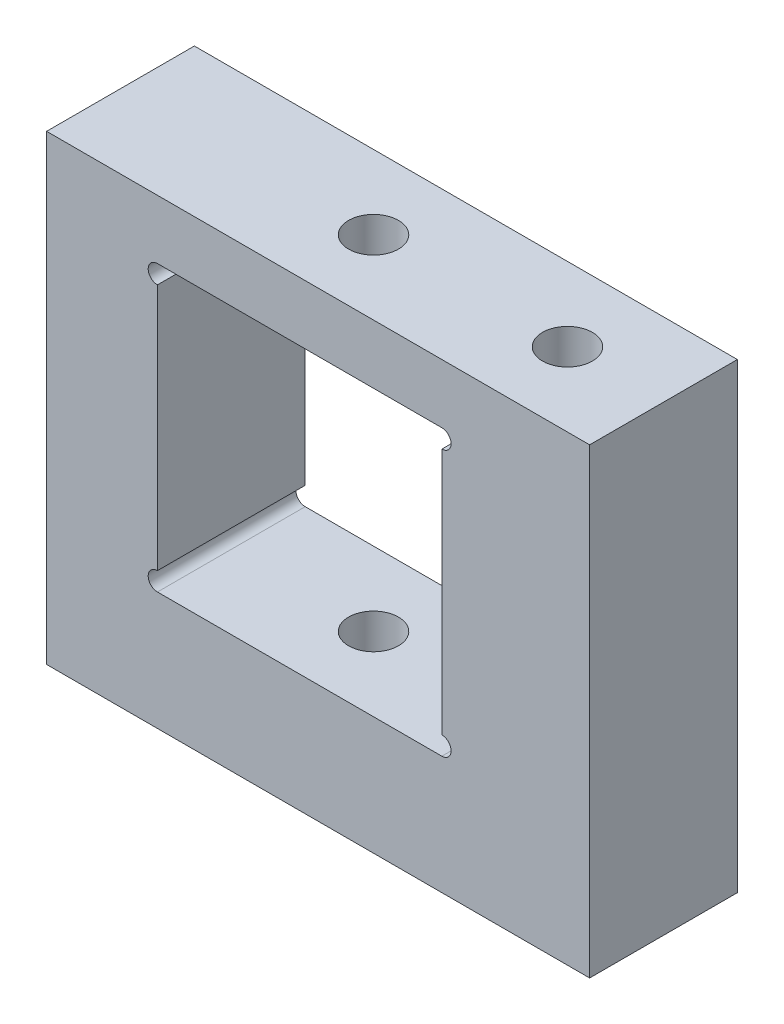
SolidWorks part; units mm, degrees
material "PLA"
ref_plane "前视基准面" through (0, 0, 0) normal (0, 0, 1) x (1, 0, 0)
ref_plane "上视基准面" through (0, 0, 0) normal (0, 1, 0) x (1, 0, 0)
ref_plane "右视基准面" through (0, 0, 0) normal (1, 0, 0) x (0, 0, -1)
sketch "草图2" plane through (0, 0, 0) normal (0, 0, 1) x (1, 0, 0)
  line L0 (-13.7, 10.9) -> (15.7, 10.9)
  line L1 (7.7, -7.7) -> (-7.7, -7.7)
  line L2 (7.7, -7.7) -> (7.7, 7.7)
  line L3 (7.7, 7.7) -> (-7.7, 7.7)
  line L4 (-7.7, -7.7) -> (-7.7, 7.7)
  line L5 (7.7, -7.7) -> (-7.7, 7.7) construction
  line L6 (7.7, 7.7) -> (-7.7, -7.7) construction
  line L7 (15.7, 10.9) -> (15.7, -14.1)
  line L8 (15.7, -14.1) -> (-13.7, -14.1)
  line L9 (-13.7, -14.1) -> (-13.7, 10.9)
  line L10 (0, 0) -> (-11.4797, 0) construction
  circle A0 centre (-7.7, 7.2) radius 0.5
  circle A1 centre (7.7, 7.2) radius 0.5
  circle A2 centre (7.7, -7.2) radius 0.5
  circle A3 centre (-7.7, -7.2) radius 0.5
  point P0 (0, 0)
  dimension "D2" = 1
  dimension "D1" = 15.4
  dimension "D3" = 6
  dimension "D4" = 10.9
  dimension "D5" = 25
  dimension "D6" = 8
extrude "凸台-拉伸1" add sketch "草图2" along normal blind 8 contours L9 L8 L7 L0 A3 L4 A0 L3 A1 L2 A2 L1
sketch "草图3" plane through (0, 10.9, 0) normal (0, 1, 0) x (1, 0, 0)
  line L0 (21, -4) -> (15.7, -4) construction
  line L1 (15.7, -8) -> (15.7, 0) construction
  circle A0 centre (10.5, -4) radius 1.35
  circle A1 centre (21, -4) radius 1.35
  circle A2 centre (0, -4) radius 1.35
  dimension "D3" = 2.7
  dimension "D1" = 10.5
  dimension "D2" = 10.5
  dimension "D4" = 10.5
extrude "切除-拉伸1" cut sketch "草图3" against normal through all and the other way through all
